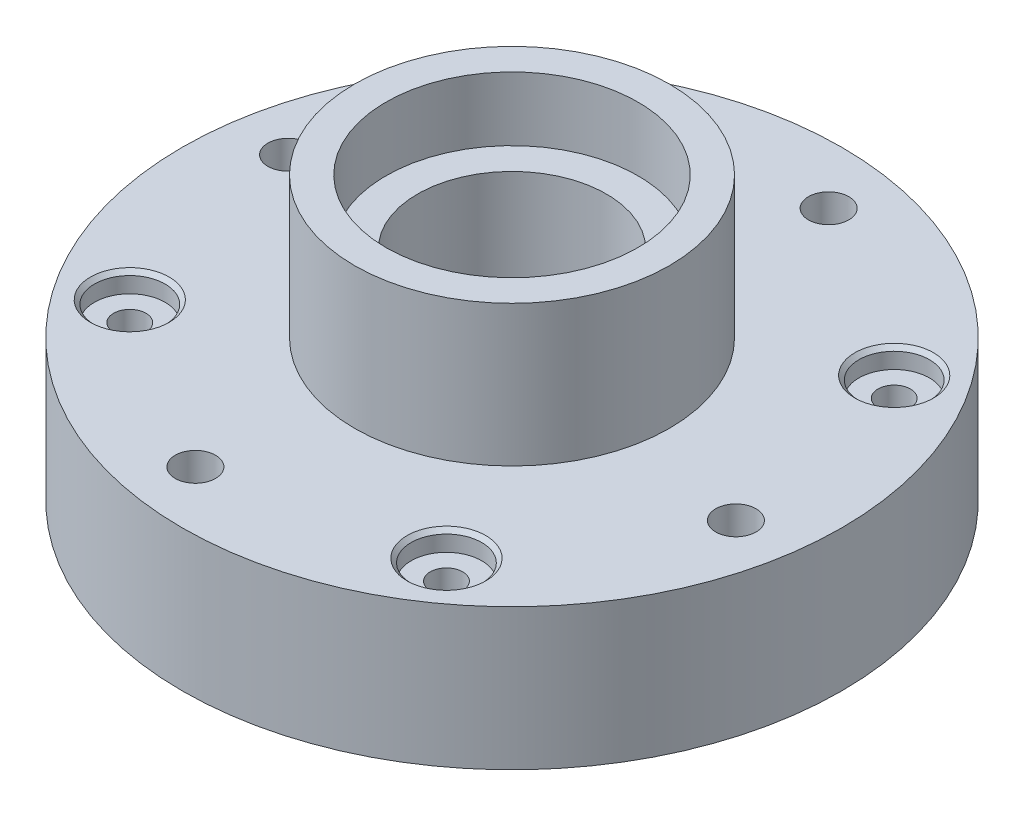
SolidWorks part; units mm, degrees
ref_plane "Front Plane" through (0, 0, 0) normal (0, 0, 1) x (1, 0, 0)
ref_plane "Top Plane" through (0, 0, 0) normal (0, 1, 0) x (1, 0, 0)
ref_plane "Right Plane" through (0, 0, 0) normal (1, 0, 0) x (0, 0, -1)
sketch "Sketch1" plane through (0, 0, 0) normal (0, 0, 1) x (1, 0, 0)
  line L0 (19.8391, 36.4265) -> (24.7675, 36.4265)
  line L1 (24.7675, 36.4265) -> (24.7675, 14.2484)
  line L2 (24.7675, 14.2484) -> (51.8879, 14.2484)
  line L3 (51.8879, 14.2484) -> (51.8879, -7.9766)
  line L4 (51.8879, -7.9766) -> (14.8707, -7.9766)
  line L5 (0, 36.4265) -> (0, -11.6461) construction
  line L6 (19.8391, 36.4265) -> (19.8391, 26.3797)
  line L7 (19.8391, 26.3797) -> (14.8707, 26.3797)
  line L8 (14.8707, 26.3797) -> (14.8707, -7.9766)
  dimension "D1" = 22.225
revolve "Revolve2" add sketch "Sketch1" angle 360 about L5
hole_wizard "1/4-20 Tapped Hole2" positions "Sketch5" profile "Sketch4" tap size "1/4-20" standard "Ansi Inch"
sketch "Sketch5" plane through (0, 14.2484, 0) normal (0, 1, 0) x (-1, 0, 0)
  point P0 (-42.5335, 7.295)
sketch "Sketch4" plane through (42.5335, 14.2484, 7.295) normal (1, 0, 0) x (0, 0, 1)
  line L0 (0, 0) -> (0, 18.0438)
  line L1 (0, 18.0438) -> (2.5527, 16.51)
  line L2 (2.5527, 16.51) -> (2.5527, 12.7)
  line L3 (2.5527, 12.7) -> (3.175, 12.7)
  line L4 (3.175, 12.7) -> (3.175, 0)
  line L5 (3.175, 0) -> (0, 0)
  line L10 (0, 18.0438) -> (-2.5527, 16.51) construction
  line L11 (0, -6.35) -> (0, 107.95) construction
  dimension "Tap Drill Dia." = 5.1054
  dimension "Tap Drill Depth" = 16.51
  dimension "Thread Major Dia." = 6.35
  dimension "Thread Depth" = 12.7
  dimension "Drill Angle" = 118
pattern_circular "CirPattern1" count 4 over 360 about axis through (0, 0, 0) along (0, 1, 0) of "1/4-20 Tapped Hole2"
sketch "Sketch6" plane through (0, 0, 0) normal (0, 1, 0) x (1, 0, 0)
  line L0 (0, 0) -> (42.5335, -7.295) construction
  line L1 (0, 0) -> (35.2341, 24.9173) construction
  dimension "D1" = 45
hole_wizard "CBORE for #10 Binding Head Machine Screw1" positions "Sketch8" profile "Sketch7" counterbore size "#10" standard "Ansi Inch" end condition through all
sketch "Sketch8" plane through (0, 14.2484, 0) normal (0, 1, 0) x (-1, 0, 0)
  point P0 (-35.2341, -24.9173)
sketch "Sketch7" plane through (35.2341, 14.2484, -24.9173) normal (1, 0, 0) x (0, 0, 1)
  line L0 (0, 0) -> (0, 22.225)
  line L1 (0, 22.225) -> (2.5527, 22.225)
  line L3 (2.5527, 22.225) -> (2.5527, 3.1242)
  line L4 (5.5562, 3.1242) -> (2.5527, 3.1242)
  line L5 (5.5562, 3.1242) -> (5.5563, 0.635)
  line L6 (5.5563, 0.635) -> (6.1913, 0)
  line L7 (6.1913, 0) -> (0, 0)
  line L8 (-5.5563, 0.635) -> (-6.1913, 0) construction
  line L11 (0, -6.35) -> (0, 107.95) construction
  dimension "Thru Hole Dia." = 5.1054
  dimension "Thru Hole Depth" = 22.225
  dimension "C'Bore Dia." = 11.1125
  dimension "C'Bore Depth" = 3.1242
  dimension "Near C'Sink Dia." = 12.3825
  dimension "Near C'Sink Angle" = 90
pattern_circular "CirPattern2" count 4 over 360 about axis through (0, 0, 0) along (0, 1, 0) of "CBORE for #10 Binding Head Machine Screw1"
